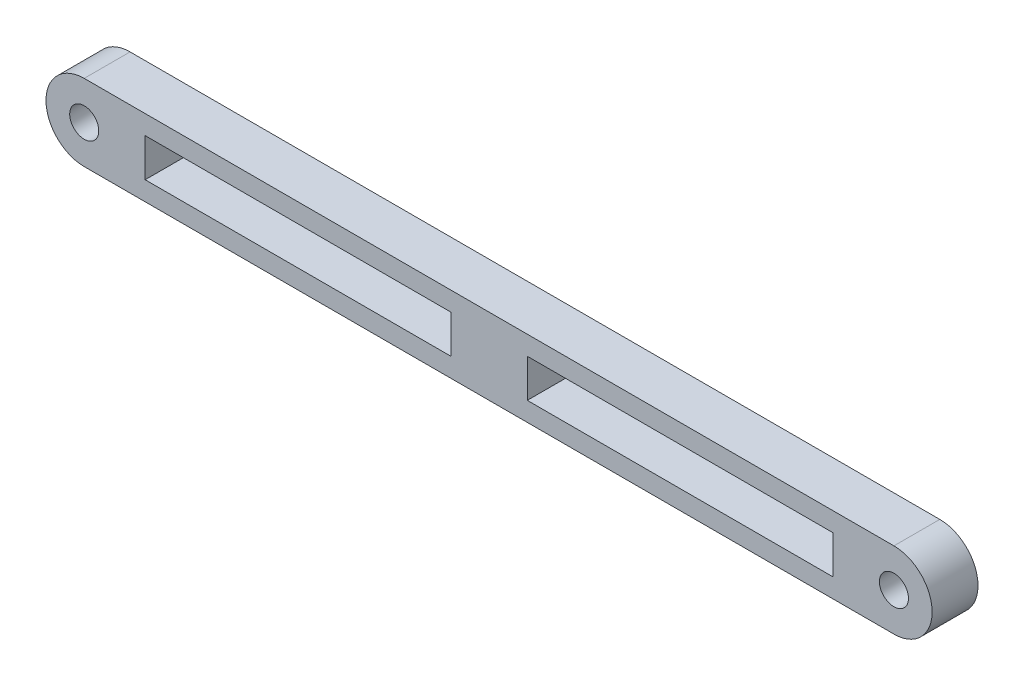
SolidWorks part; units mm, degrees
material "MDF"
ref_plane "Front Plane" through (0, 0, 0) normal (0, 0, 1) x (1, 0, 0)
ref_plane "Top Plane" through (0, 0, 0) normal (0, 1, 0) x (1, 0, 0)
ref_plane "Right Plane" through (0, 0, 0) normal (1, 0, 0) x (0, 0, -1)
sketch "Sketch1" plane through (0, 0, 0) normal (0, 0, 1) x (1, 0, 0)
  line L0 (0, -5) -> (0, 5) construction
  line L1 (-52.9741, 5) -> (52.9741, 5)
  line L2 (-52.9741, -5) -> (52.9741, -5)
  line L3 (52.9741, 0) -> (-52.9741, 0) construction
  arc A0 (52.9741, 5) -> (52.9741, -5) centre (52.9741, 0) cw
  arc A1 (-52.9741, 5) -> (-52.9741, -5) centre (-52.9741, 0) ccw
  circle A2 centre (-52.9741, 0) radius 1.9
  circle A3 centre (52.9741, 0) radius 1.9
  point P4 (0, 0)
  point P8 (0, 5)
  point P11 (0, -5)
  point P13 (0, 0)
  dimension "D3" = 3.8
  dimension "D4" = 3.8
  dimension "D1" = 10
  dimension "D2" = 105.9481
extrude "Boss-Extrude1" add sketch "Sketch1" along normal blind 6
sketch "Sketch2" plane through (0, 0, 6) normal (0, 0, 1) x (1, 0, 0)
  line L0 (25, 0) -> (-25, 0) construction
  line L2 (-45, -2.5) -> (-5, -2.5)
  line L3 (-45, -2.5) -> (-45, 2.5)
  line L4 (-45, 2.5) -> (-5, 2.5)
  line L5 (-5, -2.5) -> (-5, 2.5)
  line L6 (-45, -2.5) -> (-5, 2.5) construction
  line L7 (-45, 2.5) -> (-5, -2.5) construction
  line L8 (5, -2.5) -> (45, -2.5)
  line L9 (5, -2.5) -> (5, 2.5)
  line L10 (5, 2.5) -> (45, 2.5)
  line L11 (45, -2.5) -> (45, 2.5)
  line L12 (5, -2.5) -> (45, 2.5) construction
  line L13 (5, 2.5) -> (45, -2.5) construction
  point P4 (0, 0)
  dimension "D1" = 5
  dimension "D2" = 5
  dimension "D3" = 50
  dimension "D4" = 40
  dimension "D5" = 40
extrude "Cut-Extrude1" cut sketch "Sketch2" against normal through all
